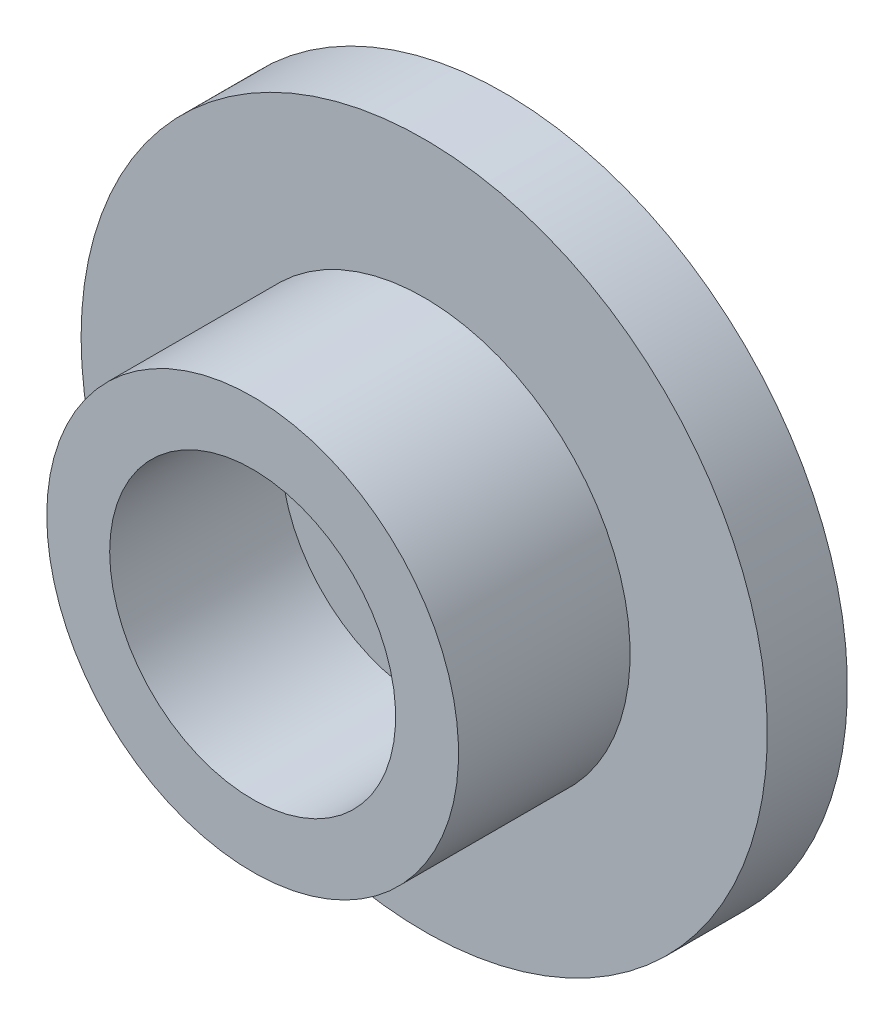
SolidWorks part; units mm, degrees
ref_plane "Спереди" through (0, 0, 0) normal (0, 0, 1) x (1, 0, 0)
ref_plane "Сверху" through (0, 0, 0) normal (0, 1, 0) x (1, 0, 0)
ref_plane "Справа" through (0, 0, 0) normal (1, 0, 0) x (0, 0, -1)
sketch "Эскиз1" plane through (0, 0, 0) normal (0, 0, 1) x (1, 0, 0)
  circle A0 centre (0, 0) radius 12.5
  circle A1 centre (0, 0) radius 18
extrude "Вытянуть1" add sketch "Эскиз1" along normal blind 7
sketch "Эскиз3" plane through (0, 0, 7) normal (0, 0, 1) x (1, 0, 0)
  circle A0 centre (0, 0) radius 12.5
  circle A1 centre (0, 0) radius 18
extrude "Вытянуть2" add sketch "Эскиз3" along normal up to surface (22 mm away)
sketch "Эскиз4" plane through (0, 0, 0) normal (0, 0, -1) x (-1, 0, 0)
  circle A0 centre (0, 0) radius 30
extrude "Вытянуть3" add sketch "Эскиз4" along normal blind 7 from offset 14
